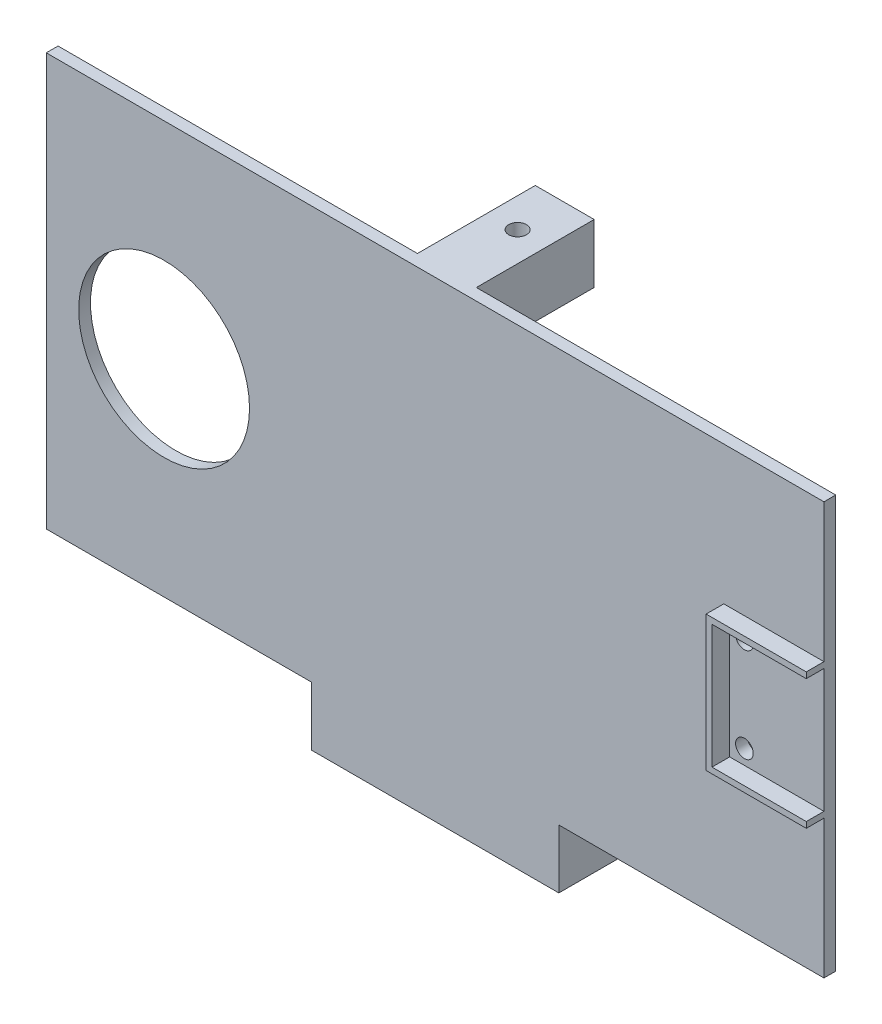
SolidWorks part; units mm, degrees
ref_plane "Front Plane" through (0, 0, 0) normal (0, 0, 1) x (1, 0, 0)
ref_plane "Top Plane" through (0, 0, 0) normal (0, 1, 0) x (1, 0, 0)
ref_plane "Right Plane" through (0, 0, 0) normal (1, 0, 0) x (0, 0, -1)
sketch "Sketch1" plane through (0, 0, 0) normal (0, 0, 1) x (1, 0, 0)
  line L0 (21, -35) -> (66, -35)
  line L1 (-66, -35) -> (-21, -35)
  line L2 (-66, -35) -> (-66, 35)
  line L3 (-66, 35) -> (66, 35)
  line L4 (66, -35) -> (66, 35)
  line L5 (-66, -35) -> (66, 35) construction
  line L6 (-66, 35) -> (66, -35) construction
  line L7 (21, -45) -> (-21, -45)
  line L8 (21, -45) -> (21, -35)
  line L10 (-21, -45) -> (-21, -35)
  line L11 (21, -45) -> (0, -35) construction
  line L12 (0, -35) -> (-21, -45) construction
  point P0 (0, 0)
  point P6 (0, -35)
  dimension "D1" = 132
  dimension "D2" = 70
  dimension "D3" = 42
  dimension "D4" = 10
extrude "Boss-Extrude1" add sketch "Sketch1" along normal blind 2
sketch "Sketch2" plane through (0, 0, 2) normal (0, 0, 1) x (1, 0, 0)
  line L0 (-66, 35) -> (-66, -35) construction
  circle A0 centre (-46, 0) radius 14.5
  point P0 (-46, 0)
  dimension "D2" = 29
  dimension "D1" = 20
extrude "Cut-Extrude1" cut sketch "Sketch2" against normal blind 2 contours A0
sketch "Sketch3" plane through (0, 0, 2) normal (0, 0, 1) x (1, 0, 0)
  line L0 (66, -35) -> (66, 35) construction
  line L4 (50, -10.5) -> (50, 10.5)
  line L7 (66, 11.5) -> (66, 10.5)
  line L8 (66, -11.5) -> (49, -11.5)
  line L10 (66, 11.5) -> (49, 11.5)
  line L11 (49, -11.5) -> (49, 11.5)
  line L14 (66, -10.5) -> (66, -11.5)
  line L15 (66, 10.5) -> (50, 10.5)
  line L16 (50.4783, -10.5) -> (49, -11.5) construction
  line L17 (50.4783, 10.5) -> (49, 11.5) construction
  line L18 (66, -10.5) -> (50, -10.5)
  point P0 (66, 0)
  point P7 (58, -5.25)
extrude "Boss-Extrude2" add sketch "Sketch3" along normal blind 3
sketch "Sketch5" plane through (0, 0, 2) normal (0, 0, 1) x (1, 0, 0)
  line L0 (50, 10.5) -> (66, 10.5) construction
  line L1 (50, -10.5) -> (50, 10.5) construction
  line L2 (66, -10.5) -> (50, -10.5) construction
  circle A0 centre (52.5, 8) radius 1.5
  circle A1 centre (52.5, -8) radius 1.5
  point P0 (52.5, 8)
  point P1 (52.5, -8)
  dimension "D5" = 3
  dimension "D6" = 3
  dimension "D1" = 2.5
  dimension "D2" = 2.5
  dimension "D3" = 2.5
  dimension "D4" = 2.5
extrude "Cut-Extrude2" cut sketch "Sketch5" against normal up to next
sketch "Sketch6" plane through (0, 0, 0) normal (0, 0, -1) x (-1, 0, 0)
  line L0 (-66, 35) -> (66, 35) construction
  line L1 (-5, 25) -> (5, 25)
  line L2 (-5, 25) -> (-5, 35)
  line L4 (5, 25) -> (5, 35)
  line L5 (-5, 25) -> (0, 35) construction
  line L6 (0, 35) -> (5, 25) construction
  line L7 (-5, 35) -> (5, 35)
  point P0 (0, 35)
extrude "Boss-Extrude3" add sketch "Sketch6" along normal blind 20
sketch "Sketch10" plane through (0, 0, 0) normal (0, 0, -1) x (-1, 0, 0)
  line L0 (21, -45) -> (-21, -45) construction
  line L2 (-21, -25) -> (21, -25)
  line L3 (-21, -25) -> (-21, -45)
  line L4 (-21, -45) -> (21, -45)
  line L5 (21, -25) -> (21, -45)
  line L6 (-21, -25) -> (21, -45) construction
  line L7 (-21, -45) -> (21, -25) construction
  point P0 (0, -35)
  point P3 (0, -35)
  dimension "D1" = 10
extrude "Boss-Extrude5" add sketch "Sketch10" along normal blind 20
sketch "Sketch11" plane through (0, -45, 0) normal (0, -1, 0) x (1, 0, 0)
  line L0 (21, -20) -> (-21, -20) construction
  line L1 (-3.9322, -7.4682) -> (-16.4083, -9.5336)
  line L2 (3.9322, -16.5318) -> (16.4083, -14.4664)
  line L3 (3.9322, -7.4682) -> (16.4083, -9.5336)
  line L4 (-3.9322, -16.5318) -> (-16.4083, -14.4665)
  arc A0 (-3.9322, -16.5318) -> (3.9322, -16.5318) centre (0, -12) ccw
  arc A1 (-16.4083, -9.5336) -> (-16.4083, -14.4665) centre (-16, -12) ccw
  arc A2 (16.4083, -14.4664) -> (16.4083, -9.5336) centre (16, -12) ccw
  arc A3 (3.9322, -7.4682) -> (-3.9322, -7.4682) centre (0, -12) ccw
  point P0 (0, -12)
  point P5 (-16, -12)
  point P6 (16, -12)
  dimension "D2" = 12
  dimension "D5" = 5
  dimension "D6" = 5
  dimension "D1" = 8
  dimension "D3" = 16
  dimension "D4" = 16
extrude "Cut-Extrude3" cut sketch "Sketch11" against normal blind 6
sketch "Sketch12" plane through (0, 35, 0) normal (0, 1, 0) x (1, 0, 0)
  line L0 (-5, 20) -> (5, 20) construction
  circle A0 centre (0, 12) radius 1.5
  point P0 (0, 12)
  dimension "D2" = 3
  dimension "D1" = 8
extrude "Cut-Extrude4" cut sketch "Sketch12" against normal up to next
